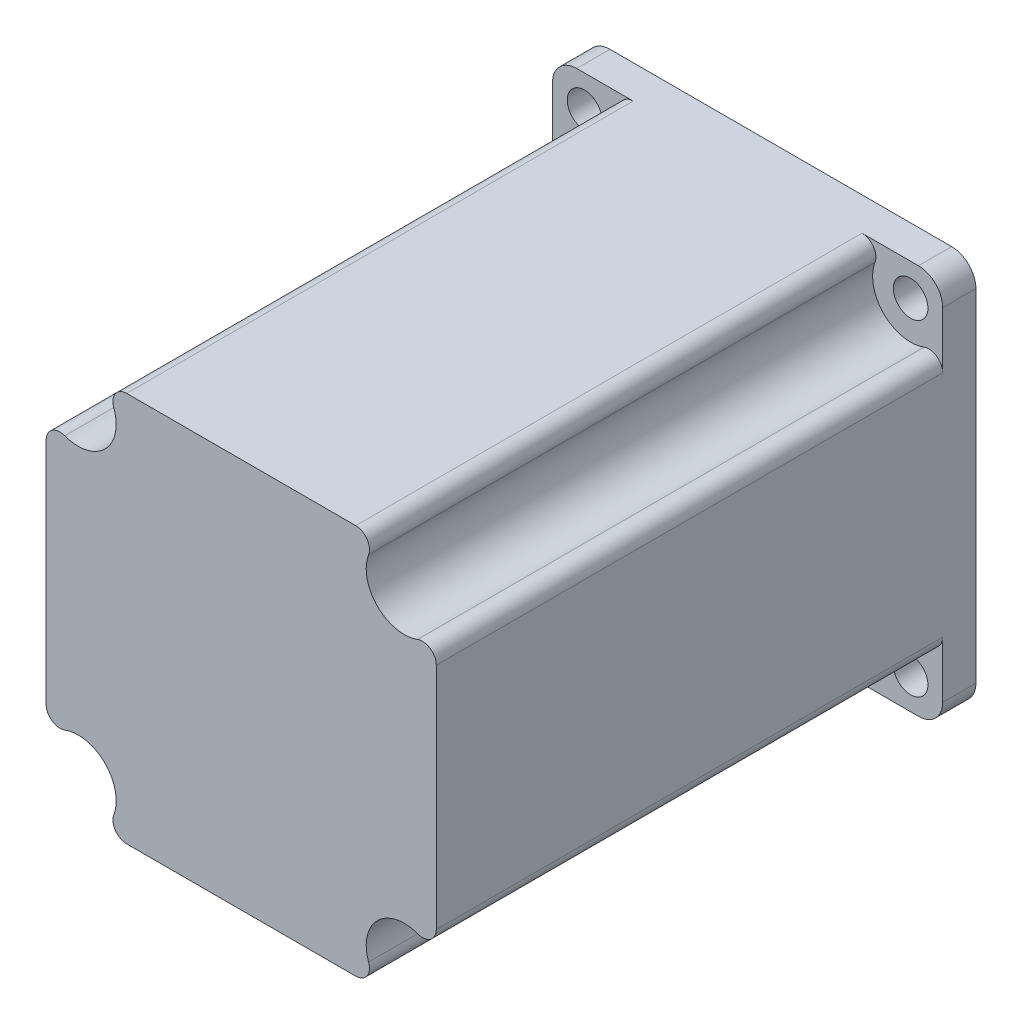
SolidWorks part; units mm, degrees
ref_plane "Front Plane" through (0, 0, 0) normal (0, 0, 1) x (1, 0, 0)
ref_plane "Top Plane" through (0, 0, 0) normal (0, 1, 0) x (1, 0, 0)
ref_plane "Right Plane" through (0, 0, 0) normal (1, 0, 0) x (0, 0, -1)
sketch "Sketch1" plane through (0, 0, 0) normal (0, 0, 1) x (1, 0, 0)
  line L0 (0, 0) -> (56.4, 0)
  line L1 (56.4, 0) -> (56.4, 56.4)
  line L2 (56.4, 56.4) -> (0, 56.4)
  line L3 (0, 56.4) -> (0, 0)
  line L4 (0, 0) -> (56.4, 56.4) construction
  line L5 (0, 56.4) -> (56.4, 0) construction
  dimension "D1" = 56.4
extrude "Boss-Extrude1" add sketch "Sketch1" along normal blind 78
sketch "Sketch7" plane through (0, 0, 78) normal (0, 0, 1) x (1, 0, 0)
  line L0 (0, 56.4) -> (56.4, 0) construction
  line L1 (56.4, 56.4) -> (0, 0) construction
fillet "Fillet1" radius 3.5 4 edges at (56.4, 0, 39) (0, 0, 39) (0, 56.4, 39) (56.4, 56.4, 39)
sketch "Sketch2" plane through (0, 0, 0) normal (0, 0, -1) x (-1, 0, 0)
  line L0 (0, 0) -> (-56.4, 56.4) construction
  circle A0 centre (-28.2, 28.2) radius 19.05
  dimension "D1" = 38.1
extrude "Boss-Extrude2" add sketch "Sketch2" along normal blind 1.6
sketch "Sketch4" plane through (0, 0, 0) normal (0, 0, -1) x (-1, 0, 0)
  line L0 (0, 0) -> (-56.4, 56.4) construction
  circle A0 centre (-28.2, 28.2) radius 3.175
  dimension "D1" = 6.35
extrude "Boss-Extrude3" add sketch "Sketch4" along normal blind 20.6
sketch "Sketch5" plane through (0, 0, 0) normal (0, 0, -1) x (-1, 0, 0)
  line L0 (0, 0) -> (-56.4, 56.4) construction
  line L1 (0, 56.4) -> (-56.4, 0) construction
  line L2 (-51.77, 51.77) -> (-4.63, 51.77) construction
  line L3 (-4.63, 51.77) -> (-4.63, 4.63) construction
  line L4 (-4.63, 4.63) -> (-51.77, 4.63) construction
  line L5 (-51.77, 4.63) -> (-51.77, 51.77) construction
  circle A0 centre (-51.77, 51.77) radius 2.5
  circle A1 centre (-4.63, 51.77) radius 2.5
  circle A2 centre (-4.63, 4.63) radius 2.5
  circle A3 centre (-51.77, 4.63) radius 2.5
  dimension "D1" = 5
  dimension "D2" = 47.14
extrude "Cut-Extrude1" cut sketch "Sketch5" against normal through all
ref_plane "Plane1" through (0, 0, 4.8) normal (0, 0, -1) x (-1, 0, 0)
sketch "Sketch8" plane through (0, 0, 78) normal (0, 0, 1) x (1, 0, 0)
  line L0 (0, 56.4) -> (56.4, 0) construction
  line L1 (56.4, 56.4) -> (0, 0) construction
  line L2 (4.63, 51.77) -> (4.63, 4.63) construction
  line L3 (4.63, 4.63) -> (51.77, 4.63) construction
  line L4 (51.77, 4.63) -> (51.77, 51.77) construction
  line L5 (51.77, 51.77) -> (4.63, 51.77) construction
  circle A0 centre (4.63, 51.77) radius 5.5
  circle A1 centre (51.77, 51.77) radius 5.5
  circle A2 centre (51.77, 4.63) radius 5.5
  circle A3 centre (4.63, 4.63) radius 5.5
  dimension "D1" = 11
extrude "Cut-Extrude2" cut sketch "Sketch8" against normal up to surface (73.2 mm away)
fillet "Fillet2" radius 2 8 edges at (7.5987, 0, 41.4) (0, 7.5987, 41.4) (48.8013, 0, 41.4) (56.4, 7.5987, 41.4) (56.4, 48.8013, 41.4) (48.8013, 56.4, 41.4) (0, 48.8013, 41.4) (7.5987, 56.4, 41.4)
